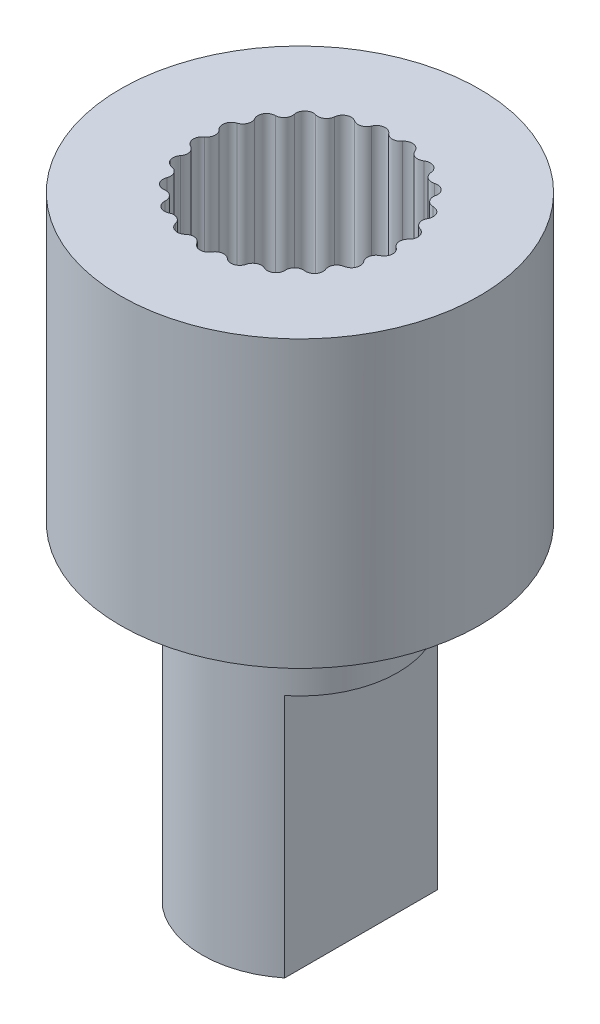
SolidWorks part; units mm, degrees
ref_plane "Front Plane" through (0, 0, 0) normal (0, 0, 1) x (1, 0, 0)
ref_plane "Top Plane" through (0, 0, 0) normal (0, 1, 0) x (1, 0, 0)
ref_plane "Right Plane" through (0, 0, 0) normal (1, 0, 0) x (0, 0, -1)
sketch "Sketch1" plane through (0, 0, 0) normal (0, 1, 0) x (1, 0, 0)
  line L0 (0, 0) -> (0, 4.4464) construction
  line L1 (0, 0) -> (0.6627, 4.3968) construction
  line L2 (0, 0) -> (1.3106, 4.2489) construction
  line L3 (0, 0) -> (1.9292, 4.0061) construction
  line L4 (0, 0) -> (2.5048, 3.6738) construction
  line L5 (0, 0) -> (3.0243, 3.2595) construction
  line L6 (0, 0) -> (3.4764, 2.7723) construction
  line L7 (0, 0) -> (3.8507, 2.2232) construction
  line L8 (0, 0) -> (4.1391, 1.6245) construction
  line L9 (0, 0) -> (4.3349, 0.9894) construction
  line L10 (0, 0) -> (4.434, 0.3323) construction
  line L11 (0, 0) -> (4.434, -0.3323) construction
  line L12 (0, 0) -> (4.3349, -0.9894) construction
  line L13 (0, 0) -> (4.1391, -1.6245) construction
  line L14 (0, 0) -> (3.8507, -2.2232) construction
  line L15 (0, 0) -> (3.4764, -2.7723) construction
  line L16 (0, 0) -> (3.0243, -3.2595) construction
  line L17 (0, 0) -> (2.5048, -3.6738) construction
  line L18 (0, 0) -> (1.9292, -4.0061) construction
  line L19 (0, 0) -> (1.3106, -4.2489) construction
  line L20 (0, 0) -> (0.6627, -4.3968) construction
  line L21 (0, 0) -> (0, -4.4464) construction
  line L22 (0, 0) -> (-0.6627, -4.3968) construction
  line L23 (0, 0) -> (-1.3106, -4.2489) construction
  line L24 (0, 0) -> (-1.9292, -4.0061) construction
  line L25 (0, 0) -> (-2.5048, -3.6738) construction
  line L26 (0, 0) -> (-3.0243, -3.2595) construction
  line L27 (0, 0) -> (-3.4764, -2.7723) construction
  line L28 (0, 0) -> (-3.8507, -2.2232) construction
  line L29 (0, 0) -> (-4.1391, -1.6245) construction
  line L30 (0, 0) -> (-4.3349, -0.9894) construction
  line L31 (0, 0) -> (-4.434, -0.3323) construction
  line L32 (0, 0) -> (-4.434, 0.3323) construction
  line L33 (0, 0) -> (-4.3349, 0.9894) construction
  line L34 (0, 0) -> (-4.1391, 1.6245) construction
  line L35 (0, 0) -> (-3.8507, 2.2232) construction
  line L36 (0, 0) -> (-3.4764, 2.7723) construction
  line L37 (0, 0) -> (-3.0243, 3.2595) construction
  line L38 (0, 0) -> (-2.5048, 3.6738) construction
  line L39 (0, 0) -> (-1.9292, 4.0061) construction
  line L40 (0, 0) -> (-1.3106, 4.2489) construction
  line L41 (0, 0) -> (-0.6627, 4.3968) construction
  circle A1 centre (0, 0) radius 2.45 construction
  circle A5 centre (0, 0) radius 3.95
  circle A14 centre (0, 0) radius 2.2653 construction
  arc A22 (-0.1666, 2.3451) -> (0, 2.2653) centre (0, 2.479) ccw
  arc A23 (-0.1666, 2.3451) -> (-0.532, 2.2901) centre (-0.3333, 2.2113) ccw
  arc A24 (-0.6677, 2.1646) -> (-0.532, 2.2901) centre (-0.7307, 2.3689) ccw
  arc A25 (0, 2.2653) -> (0.1666, 2.3451) centre (0, 2.479) ccw
  arc A26 (0.532, 2.2901) -> (0.1666, 2.3451) centre (0.3333, 2.2113) ccw
  arc A27 (0.532, 2.2901) -> (0.6677, 2.1646) centre (0.7307, 2.3689) ccw
  arc A28 (0.6677, 2.1646) -> (0.8505, 2.1918) centre (0.7307, 2.3689) ccw
  arc A29 (1.1834, 2.0315) -> (0.8505, 2.1918) centre (0.9703, 2.0148) ccw
  arc A30 (1.1834, 2.0315) -> (1.2761, 1.8716) centre (1.3965, 2.0483) ccw
  arc A31 (1.2761, 1.8716) -> (1.4588, 1.8438) centre (1.3965, 2.0483) ccw
  arc A32 (1.7296, 1.5925) -> (1.4588, 1.8438) centre (1.521, 1.6393) ccw
  arc A33 (1.7296, 1.5925) -> (1.7711, 1.4124) centre (1.9382, 1.5456) ccw
  arc A34 (1.7711, 1.4124) -> (1.9374, 1.3319) centre (1.9382, 1.5456) ccw
  arc A35 (2.1221, 1.0119) -> (1.9374, 1.3319) centre (1.9366, 1.1181) ccw
  arc A36 (2.1221, 1.0119) -> (2.1087, 0.8276) centre (2.3077, 0.9057) ccw
  arc A37 (2.1087, 0.8276) -> (2.2439, 0.7016) centre (2.3077, 0.9057) ccw
  arc A38 (2.3261, 0.3414) -> (2.2439, 0.7016) centre (2.1802, 0.4976) ccw
  arc A39 (2.3261, 0.3414) -> (2.2589, 0.1693) centre (2.4721, 0.1853) ccw
  arc A40 (2.2589, 0.1693) -> (2.351, 0.0091) centre (2.4721, 0.1853) ccw
  arc A41 (2.3234, -0.3594) -> (2.351, 0.0091) centre (2.23, -0.1671) ccw
  arc A42 (2.3234, -0.3594) -> (2.2085, -0.5041) centre (2.4169, -0.5516) ccw
  arc A43 (2.2085, -0.5041) -> (2.2493, -0.6843) centre (2.4169, -0.5516) ccw
  arc A44 (2.1143, -1.0283) -> (2.2493, -0.6843) centre (2.0817, -0.817) ccw
  arc A45 (2.1143, -1.0283) -> (1.9618, -1.1326) centre (2.1469, -1.2395) ccw
  arc A46 (1.9618, -1.1326) -> (1.9476, -1.3169) centre (2.1469, -1.2395) ccw
  arc A47 (1.7173, -1.6058) -> (1.9476, -1.3169) centre (1.7484, -1.3943) ccw
  arc A48 (1.7173, -1.6058) -> (1.5408, -1.6606) centre (1.6862, -1.8173) ccw
  arc A49 (1.5408, -1.6606) -> (1.4729, -1.8325) centre (1.6862, -1.8173) ccw
  arc A50 (1.1677, -2.0406) -> (1.4729, -1.8325) centre (1.2597, -1.8477) ccw
  arc A51 (1.1677, -2.0406) -> (0.9829, -2.0409) centre (1.0756, -2.2335) ccw
  arc A52 (0.9829, -2.0409) -> (0.8674, -2.1852) centre (1.0756, -2.2335) ccw
  arc A53 (0.5143, -2.2941) -> (0.8674, -2.1852) centre (0.6591, -2.1369) ccw
  arc A54 (0.5143, -2.2941) -> (0.3376, -2.24) centre (0.3695, -2.4513) ccw
  arc A55 (0.3376, -2.24) -> (0.1847, -2.3438) centre (0.3695, -2.4513) ccw
  arc A56 (-0.1847, -2.3438) -> (0.1847, -2.3438) centre (0, -2.2362) ccw
  arc A57 (-0.1847, -2.3438) -> (-0.3376, -2.24) centre (-0.3695, -2.4513) ccw
  arc A58 (-0.3376, -2.24) -> (-0.5143, -2.2941) centre (-0.3695, -2.4513) ccw
  arc A59 (-0.8674, -2.1852) -> (-0.5143, -2.2941) centre (-0.6591, -2.1369) ccw
  arc A60 (-0.8674, -2.1852) -> (-0.9829, -2.0409) centre (-1.0756, -2.2335) ccw
  arc A61 (-0.9829, -2.0409) -> (-1.1677, -2.0406) centre (-1.0756, -2.2335) ccw
  arc A62 (-1.4729, -1.8325) -> (-1.1677, -2.0406) centre (-1.2597, -1.8477) ccw
  arc A63 (-1.4729, -1.8325) -> (-1.5408, -1.6606) centre (-1.6862, -1.8173) ccw
  arc A64 (-1.5408, -1.6606) -> (-1.7173, -1.6058) centre (-1.6862, -1.8173) ccw
  arc A65 (-1.9476, -1.3169) -> (-1.7173, -1.6058) centre (-1.7484, -1.3943) ccw
  arc A66 (-1.9476, -1.3169) -> (-1.9618, -1.1326) centre (-2.1469, -1.2395) ccw
  arc A67 (-1.9618, -1.1326) -> (-2.1143, -1.0283) centre (-2.1469, -1.2395) ccw
  arc A68 (-2.2493, -0.6843) -> (-2.1143, -1.0283) centre (-2.0817, -0.817) ccw
  arc A69 (-2.2493, -0.6843) -> (-2.2085, -0.5041) centre (-2.4169, -0.5516) ccw
  arc A70 (-2.2085, -0.5041) -> (-2.3234, -0.3594) centre (-2.4169, -0.5516) ccw
  arc A71 (-2.351, 0.0091) -> (-2.3234, -0.3594) centre (-2.23, -0.1671) ccw
  arc A72 (-2.351, 0.0091) -> (-2.2589, 0.1693) centre (-2.4721, 0.1853) ccw
  arc A73 (-2.2589, 0.1693) -> (-2.3261, 0.3414) centre (-2.4721, 0.1853) ccw
  arc A74 (-2.2439, 0.7016) -> (-2.3261, 0.3414) centre (-2.1802, 0.4976) ccw
  arc A75 (-2.2439, 0.7016) -> (-2.1087, 0.8276) centre (-2.3077, 0.9057) ccw
  arc A76 (-2.1087, 0.8276) -> (-2.1221, 1.0119) centre (-2.3077, 0.9057) ccw
  arc A77 (-1.9374, 1.3319) -> (-2.1221, 1.0119) centre (-1.9366, 1.1181) ccw
  arc A78 (-1.9374, 1.3319) -> (-1.7711, 1.4124) centre (-1.9382, 1.5456) ccw
  arc A79 (-1.7711, 1.4124) -> (-1.7296, 1.5925) centre (-1.9382, 1.5456) ccw
  arc A80 (-1.4588, 1.8438) -> (-1.7296, 1.5925) centre (-1.521, 1.6393) ccw
  arc A81 (-1.4588, 1.8438) -> (-1.2761, 1.8716) centre (-1.3965, 2.0483) ccw
  arc A82 (-1.2761, 1.8716) -> (-1.1834, 2.0315) centre (-1.3965, 2.0483) ccw
  arc A83 (-0.8505, 2.1918) -> (-1.1834, 2.0315) centre (-0.9703, 2.0148) ccw
  arc A84 (-0.8505, 2.1918) -> (-0.6677, 2.1646) centre (-0.7307, 2.3689) ccw
  point P27 (0, 0)
  point P50 (0, 0)
  point P198 (0, 0)
  dimension "D1" = 1.5
  dimension "D2" = 4.9
  dimension "D3" = 42
  dimension "D4" = 2.2362
  dimension "D5" = 4.5305
  dimension "D6" = 4.5305
  dimension "D7" = 21
extrude "Boss-Extrude1" add sketch "Sketch1" along normal blind 5
sketch "Sketch2" plane through (0, 0, 0) normal (0, -1, 0) x (1, 0, 0)
  circle A0 centre (0, 0) radius 4.4
  dimension "D1" = 8.8
extrude "Boss-Extrude2" add sketch "Sketch2" along normal blind 2
sketch "Sketch4" plane through (0, -2, 0) normal (0, -1, 0) x (1, 0, 0)
  circle A0 centre (0, 0) radius 2.4
  dimension "D1" = 4.8
extrude "Boss-Extrude3" add sketch "Sketch4" along normal blind 2
sketch "Sketch5" plane through (0, -4, 0) normal (0, -1, 0) x (1, 0, 0)
  line L2 (-1.5, 1.8735) -> (-1.5, -1.8735)
  line L4 (1.5, 1.8735) -> (1.5, -1.8735)
  line L5 (-1.1513, 2.1058) -> (1.1513, -2.1058) construction
  line L6 (-1.1513, -2.1058) -> (1.1513, 2.1058) construction
  circle A0 centre (0, 0) radius 2.4
  point P0 (0, 0)
  circle M3 centre (0, 0) radius 2.4
extrude "Boss-Extrude4" add sketch "Sketch5" along normal blind 6 contours L4 L2 M3
sketch "Sketch6" plane through (0, 0, 0) normal (0, 1, 0) x (1, 0, 0)
  circle A0 centre (0, 0) radius 4.4
  circle A1 centre (0, 0) radius 3.95
extrude "Boss-Extrude5" add sketch "Sketch6" along normal blind 5
equation "\"r0.247\"=0.713093"
